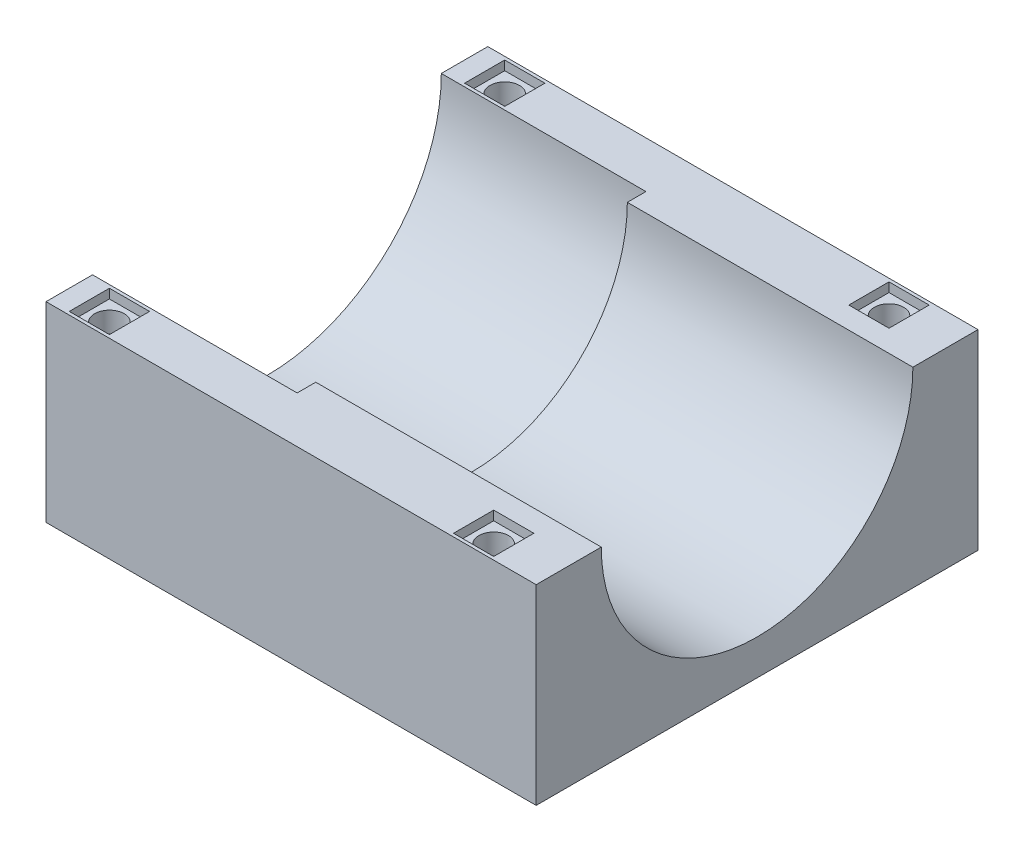
SolidWorks part; units mm, degrees
ref_plane "Alzado" through (0, 0, 0) normal (0, 0, 1) x (1, 0, 0)
ref_plane "Planta" through (0, 0, 0) normal (0, 1, 0) x (1, 0, 0)
ref_plane "Vista lateral" through (0, 0, 0) normal (1, 0, 0) x (0, 0, -1)
sketch "Croquis1" plane through (0, 0, 0) normal (1, 0, 0) x (0, 0, -1)
  line L0 (-23.75, 0) -> (-18.75, 0)
  line L1 (-23.75, 0) -> (-23.75, -20.5557)
  line L2 (23.75, 0) -> (23.75, -20.5557)
  line L3 (-23.75, -20.5557) -> (23.75, -20.5557)
  line L4 (18.75, 0) -> (23.75, 0)
  arc A0 (-18.75, 0) -> (18.75, 0) centre (0, 0) ccw
  dimension "D1" = 37.5
  dimension "D2" = 5
  dimension "D3" = 5
extrude "Saliente-Extruir1" add sketch "Croquis1" along normal blind 22
sketch "Croquis2" plane through (22, 0, 0) normal (1, 0, 0) x (0, 0, -1)
  line L0 (16.75, 0) -> (23.75, 0)
  line L1 (-23.75, 0) -> (-16.75, 0)
  line L2 (-23.75, 0) -> (-23.75, -20.5557)
  line L3 (-23.75, -20.5557) -> (23.75, -20.5557)
  line L4 (23.75, 0) -> (23.75, -20.5557)
  line L5 (-23.75, 0) -> (23.75, -20.5557) construction
  line L6 (-23.75, -20.5557) -> (23.75, 0) construction
  arc A0 (-16.75, 0) -> (16.75, 0) centre (0, 0) ccw
  point P7 (0, -10.2778)
  dimension "D1" = 33.5
extrude "Saliente-Extruir2" add sketch "Croquis2" along normal blind 30.7
sketch "Croquis4" plane through (0, 0, 0) normal (0, 1, 0) x (1, 0, 0)
  circle A0 centre (4.3181, 21.25) radius 1.585
  circle A1 centre (45.6312, 21.25) radius 1.585
  dimension "D1" = 3.17
  dimension "D2" = 3.17
extrude "Cortar-Extruir2" cut sketch "Croquis4" against normal up to next
mirror "Simetría1" about plane through (0, 0, 0) normal (0, 0, 1) of "Cortar-Extruir2"
sketch "Croquis5" plane through (0, 0, 0) normal (0, 1, 0) x (1, 0, 0)
  line L1 (6.4781, -23.4076) -> (2.1581, -23.4076)
  line L2 (6.4781, -23.4076) -> (6.4781, -19.0924)
  line L3 (6.4781, -19.0924) -> (2.1581, -19.0924)
  line L4 (2.1581, -23.4076) -> (2.1581, -19.0924)
  line L5 (6.4781, -23.4076) -> (2.1581, -19.0924) construction
  line L6 (6.4781, -19.0924) -> (2.1581, -23.4076) construction
  line L7 (43.4712, -23.41) -> (47.7912, -23.41)
  line L8 (43.4712, -23.41) -> (43.4712, -19.09)
  line L9 (43.4712, -19.09) -> (47.7912, -19.09)
  line L10 (47.7912, -23.41) -> (47.7912, -19.09)
  line L11 (43.4712, -23.41) -> (47.7912, -19.09) construction
  line L12 (43.4712, -19.09) -> (47.7912, -23.41) construction
  point P0 (4.3181, -21.25)
  point P5 (45.6312, -21.25)
  dimension "D1" = 4.3151
  dimension "D2" = 4.32
  dimension "D3" = 4.32
  dimension "D4" = 4.32
extrude "Cortar-Extruir3" cut sketch "Croquis5" against normal blind 1
sketch "Croquis6" plane through (0, -20.5557, 0) normal (0, -1, 0) x (1, 0, 0)
  line L1 (2.1581, 23.41) -> (6.4781, 23.41)
  line L2 (2.1581, 23.41) -> (2.1581, 19.09)
  line L3 (2.1581, 19.09) -> (6.4781, 19.09)
  line L4 (6.4781, 23.41) -> (6.4781, 19.09)
  line L5 (2.1581, 23.41) -> (6.4781, 19.09) construction
  line L6 (2.1581, 19.09) -> (6.4781, 23.41) construction
  line L7 (43.4712, 23.41) -> (47.7912, 23.41)
  line L8 (43.4712, 23.41) -> (43.4712, 19.09)
  line L9 (43.4712, 19.09) -> (47.7912, 19.09)
  line L10 (47.7912, 23.41) -> (47.7912, 19.09)
  line L11 (43.4712, 23.41) -> (47.7912, 19.09) construction
  line L12 (43.4712, 19.09) -> (47.7912, 23.41) construction
  point P0 (4.3181, 21.25)
  point P5 (45.6312, 21.25)
  dimension "D1" = 4.32
  dimension "D2" = 4.32
  dimension "D3" = 4.32
  dimension "D4" = 4.32
extrude "Cortar-Extruir4" cut sketch "Croquis6" against normal blind 1
mirror "Simetría2" about plane through (0, 0, 0) normal (0, 0, 1) of "Cortar-Extruir3", "Cortar-Extruir4"
